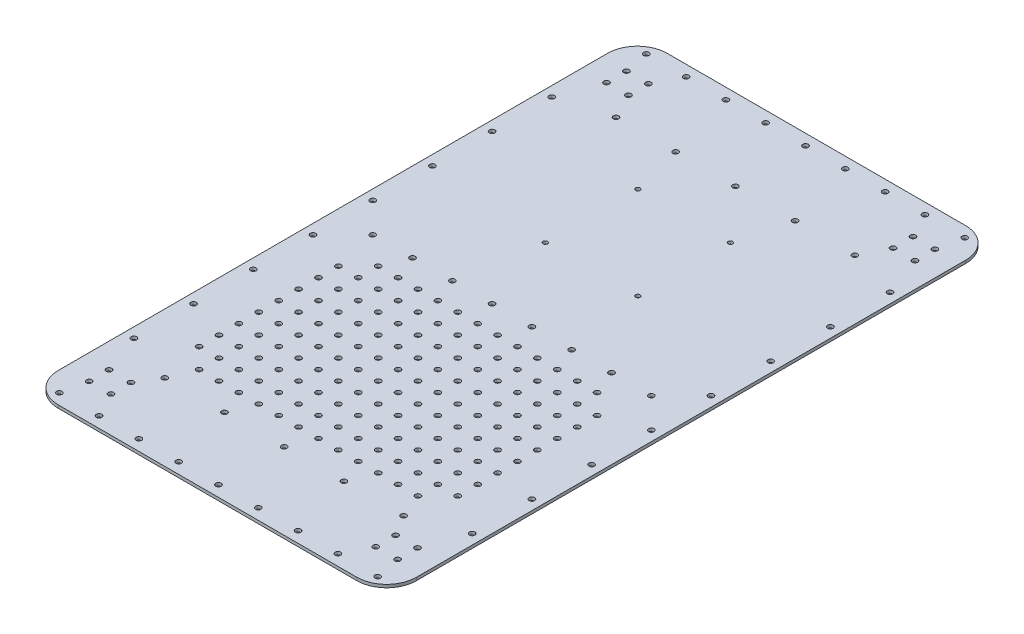
SolidWorks part; units mm, degrees
ref_plane "前视基准面" through (0, 0, 0) normal (0, 0, 1) x (1, 0, 0)
ref_plane "上视基准面" through (0, 0, 0) normal (0, 1, 0) x (1, 0, 0)
ref_plane "右视基准面" through (0, 0, 0) normal (1, 0, 0) x (0, 0, -1)
sketch "Sketch1" plane through (0, 0, 0) normal (0, 1, 0) x (1, 0, 0)
  line L0 (0, 430.9523) -> (0, 0) construction
  line L1 (-180, 306) -> (180, 306)
  line L2 (-180, 306) -> (-180, -306)
  line L3 (-180, -306) -> (180, -306)
  line L4 (180, 306) -> (180, -306)
  line L5 (-180, 306) -> (180, -306) construction
  line L6 (-180, -306) -> (180, 306) construction
  line L7 (133, -250) -> (155, -250) construction
  line L8 (133, -250) -> (133, -270) construction
  line L9 (133, -270) -> (155, -270) construction
  line L10 (155, -250) -> (155, -270) construction
  line L11 (133, -250) -> (155, -270) construction
  line L12 (133, -270) -> (155, -250) construction
  line L13 (0, 0) -> (392.7159, 0) construction
  circle A0 centre (133, -250) radius 2.75
  circle A1 centre (155, -250) radius 2.75
  circle A2 centre (133, -270) radius 2.75
  circle A3 centre (155, -270) radius 2.75
  circle A4 centre (155, 270) radius 2.75
  circle A5 centre (133, 270) radius 2.75
  circle A6 centre (155, 250) radius 2.75
  circle A7 centre (133, 250) radius 2.75
  circle A8 centre (-155, 250) radius 2.75
  circle A9 centre (-133, 250) radius 2.75
  circle A10 centre (-155, 270) radius 2.75
  circle A11 centre (-133, 270) radius 2.75
  circle A12 centre (-155, -270) radius 2.75
  circle A13 centre (-133, -270) radius 2.75
  circle A14 centre (-155, -250) radius 2.75
  circle A15 centre (-133, -250) radius 2.75
  point P0 (0, 0)
  point P6 (144, -260)
  dimension "D5" = 5.5
  dimension "D1" = 612
  dimension "D2" = 360
  dimension "D3" = 22
  dimension "D4" = 20
  dimension "D6" = 46
  dimension "D7" = 36
extrude "Boss-Extrude1" add sketch "Sketch1" along normal blind 3
sketch "草图1" plane through (0, 3, 0) normal (0, 1, 0) x (1, 0, 0)
  line L0 (-170, 306) -> (-170, -306) construction
  line L1 (180, 306) -> (-180, 306) construction
  line L2 (-180, -306) -> (180, -306) construction
  line L3 (-180, 306) -> (-180, -306) construction
  line L4 (0, 306) -> (0, -306) construction
  line L5 (-280.0781, 0) -> (279.3653, 0) construction
  circle A0 centre (-170, 210) radius 2.75
  circle A1 centre (-170, 150) radius 2.75
  circle A2 centre (-170, 90) radius 2.75
  circle A3 centre (-170, 30) radius 2.75
  circle A4 centre (-170, -30) radius 2.75
  circle A5 centre (-170, -90) radius 2.75
  circle A6 centre (-170, -150) radius 2.75
  circle A7 centre (-170, -210) radius 2.75
  circle A8 centre (170, -210) radius 2.75
  circle A9 centre (170, -150) radius 2.75
  circle A10 centre (170, -90) radius 2.75
  circle A11 centre (170, -30) radius 2.75
  circle A12 centre (170, 30) radius 2.75
  circle A13 centre (170, 90) radius 2.75
  circle A14 centre (170, 150) radius 2.75
  circle A15 centre (170, 210) radius 2.75
  dimension "D2" = 5.5
  dimension "D1" = 10
  dimension "D3" = 60
  dimension "D4" = 8
extrude "切除-拉伸1" cut sketch "草图1" against normal through all
sketch "Sketch2" plane through (0, 3, 0) normal (0, 1, 0) x (1, 0, 0)
  line L0 (-180, -295) -> (180, -295) construction
  line L1 (-180, 306) -> (-180, -306) construction
  line L2 (180, -306) -> (180, 306) construction
  line L3 (-180, -306) -> (180, -306) construction
  line L4 (-329.001, 0) -> (494.6921, 0) construction
  line L5 (-180, 295) -> (180, 295) construction
  line L6 (0, 129.5767) -> (0, -107.5451) construction
  circle A0 centre (-160, -295) radius 2.75
  circle A1 centre (-120, -295) radius 2.75
  circle A2 centre (-80, -295) radius 2.75
  circle A3 centre (-40, -295) radius 2.75
  circle A4 centre (0, -295) radius 2.75
  circle A5 centre (40, -295) radius 2.75
  circle A6 centre (80, -295) radius 2.75
  circle A7 centre (120, -295) radius 2.75
  circle A8 centre (160, -295) radius 2.75
  circle A20 centre (510, 295) radius 2.75
  circle A21 centre (470, 295) radius 2.75
  circle A22 centre (430, 295) radius 2.75
  circle A23 centre (390, 295) radius 2.75
  circle A24 centre (350, 295) radius 2.75
  circle A25 centre (310, 295) radius 2.75
  circle A26 centre (270, 295) radius 2.75
  circle A27 centre (230, 295) radius 2.75
  circle A28 centre (190, 295) radius 2.75
  circle A29 centre (160, 295) radius 2.75
  circle A30 centre (120, 295) radius 2.75
  circle A31 centre (80, 295) radius 2.75
  circle A32 centre (40, 295) radius 2.75
  circle A33 centre (0, 295) radius 2.75
  circle A34 centre (-40, 295) radius 2.75
  circle A35 centre (-80, 295) radius 2.75
  circle A36 centre (-120, 295) radius 2.75
  circle A37 centre (-160, 295) radius 2.75
  circle A40 centre (-20, 0) radius 2.75
  circle A41 centre (-60, 0) radius 2.75
  circle A42 centre (-100, 0) radius 2.75
  circle A43 centre (-140, 0) radius 2.75
  circle A44 centre (140, 0) radius 2.75
  circle A45 centre (100, 0) radius 2.75
  circle A46 centre (60, 0) radius 2.75
  circle A47 centre (20, 0) radius 2.75
  dimension "D2" = 5.5
  dimension "D6" = 5.5
  dimension "D1" = 11
  dimension "D3" = 20
  dimension "D5" = 40
  dimension "D7" = 20
  dimension "D9" = 40
  dimension "D4" = 9
  dimension "D8" = 4
extrude "Cut-Extrude1" cut sketch "Sketch2" against normal through all
fillet "Fillet1" radius 30 4 edges at (-180, 1.5, 306) (180, 1.5, 306) (180, 1.5, -306) (-180, 1.5, -306)
sketch "Sketch3" plane through (0, 3, 0) normal (0, 1, 0) x (1, 0, 0)
  line L0 (0, 424.2125) -> (0, -501.4745) construction
  line L1 (-336.746, 0) -> (500.0168, 0) construction
  line L2 (0, 173) -> (0, -28.2463) construction
  line L3 (-46.5, 173) -> (46.5, 173) construction
  line L4 (-46.5, 173) -> (-46.5, 80) construction
  line L5 (-46.5, 80) -> (46.5, 80) construction
  line L6 (46.5, 173) -> (46.5, 80) construction
  circle A0 centre (-46.5, 173) radius 2.25
  circle A1 centre (46.5, 173) radius 2.25
  circle A2 centre (-46.5, 80) radius 2.25
  circle A3 centre (46.5, 80) radius 2.25
  dimension "D5" = 4.5
  dimension "D1" = 93
  dimension "D2" = 93
  dimension "D3" = 80
extrude "Cut-Extrude2" cut sketch "Sketch3" against normal through all both and the other way through all
sketch "Sketch5" plane through (0, 3, 0) normal (0, 1, 0) x (1, 0, 0)
  line L0 (0, 0) -> (0, -337.371) construction
  line L1 (-232.7509, -4.5) -> (285.177, -4.5) construction
  line L2 (133, -250) -> (133, -270) construction
  line L3 (-110, -224.5) -> (110, -224.5) construction
  line L4 (-150, -306) -> (150, -306) construction
  line L5 (-180, 0) -> (342.3695, 0) construction
  line L6 (-180, 276) -> (-180, -276) construction
  line L7 (-194.3384, -229) -> (315.9326, -229) construction
  circle A0 centre (-10, -4.5) radius 2.75 construction
  circle A1 centre (-30, -4.5) radius 2.75 construction
  circle A2 centre (-50, -4.5) radius 2.75 construction
  circle A3 centre (-70, -4.5) radius 2.75 construction
  circle A4 centre (-90, -4.5) radius 2.75 construction
  circle A5 centre (-110, -4.5) radius 2.75 construction
  circle A6 centre (-130, -4.5) radius 2.75 construction
  circle A7 centre (-30, -24.5) radius 2.75
  circle A8 centre (-50, -24.5) radius 2.75
  circle A9 centre (-70, -24.5) radius 2.75
  circle A10 centre (-90, -24.5) radius 2.75
  circle A11 centre (-110, -24.5) radius 2.75
  circle A12 centre (-130, -24.5) radius 2.75 construction
  circle A13 centre (-30, -44.5) radius 2.75
  circle A14 centre (-50, -44.5) radius 2.75
  circle A15 centre (-70, -44.5) radius 2.75
  circle A16 centre (-90, -44.5) radius 2.75
  circle A17 centre (-110, -44.5) radius 2.75
  circle A18 centre (-130, -44.5) radius 2.75
  circle A19 centre (-30, -64.5) radius 2.75
  circle A20 centre (-50, -64.5) radius 2.75
  circle A21 centre (-70, -64.5) radius 2.75
  circle A22 centre (-90, -64.5) radius 2.75
  circle A23 centre (-110, -64.5) radius 2.75
  circle A24 centre (-130, -64.5) radius 2.75
  circle A25 centre (-30, -84.5) radius 2.75
  circle A26 centre (-50, -84.5) radius 2.75
  circle A27 centre (-70, -84.5) radius 2.75
  circle A28 centre (-90, -84.5) radius 2.75
  circle A29 centre (-110, -84.5) radius 2.75
  circle A30 centre (-130, -84.5) radius 2.75
  circle A31 centre (-30, -104.5) radius 2.75
  circle A32 centre (-50, -104.5) radius 2.75
  circle A33 centre (-70, -104.5) radius 2.75
  circle A34 centre (-90, -104.5) radius 2.75
  circle A35 centre (-110, -104.5) radius 2.75
  circle A36 centre (-130, -104.5) radius 2.75
  circle A37 centre (-30, -124.5) radius 2.75
  circle A38 centre (-50, -124.5) radius 2.75
  circle A39 centre (-70, -124.5) radius 2.75
  circle A40 centre (-90, -124.5) radius 2.75
  circle A41 centre (-110, -124.5) radius 2.75
  circle A42 centre (-130, -124.5) radius 2.75
  circle A43 centre (-30, -144.5) radius 2.75
  circle A44 centre (-50, -144.5) radius 2.75
  circle A45 centre (-70, -144.5) radius 2.75
  circle A46 centre (-90, -144.5) radius 2.75
  circle A47 centre (-110, -144.5) radius 2.75
  circle A48 centre (-130, -144.5) radius 2.75
  circle A49 centre (-30, -164.5) radius 2.75
  circle A50 centre (-50, -164.5) radius 2.75
  circle A51 centre (-70, -164.5) radius 2.75
  circle A52 centre (-90, -164.5) radius 2.75
  circle A53 centre (-110, -164.5) radius 2.75
  circle A54 centre (-130, -164.5) radius 2.75
  circle A55 centre (-30, -184.5) radius 2.75
  circle A56 centre (-50, -184.5) radius 2.75
  circle A57 centre (-70, -184.5) radius 2.75
  circle A58 centre (-90, -184.5) radius 2.75
  circle A59 centre (-110, -184.5) radius 2.75
  circle A60 centre (-130, -184.5) radius 2.75
  circle A61 centre (-10, -24.5) radius 2.75
  circle A62 centre (-10, -44.5) radius 2.75
  circle A63 centre (-10, -64.5) radius 2.75
  circle A64 centre (-10, -84.5) radius 2.75
  circle A65 centre (-10, -104.5) radius 2.75
  circle A66 centre (-10, -124.5) radius 2.75
  circle A67 centre (-10, -144.5) radius 2.75
  circle A68 centre (-10, -164.5) radius 2.75
  circle A69 centre (-10, -184.5) radius 2.75
  circle A70 centre (10, -184.5) radius 2.75
  circle A71 centre (10, -164.5) radius 2.75
  circle A72 centre (10, -144.5) radius 2.75
  circle A73 centre (10, -124.5) radius 2.75
  circle A74 centre (10, -104.5) radius 2.75
  circle A75 centre (10, -84.5) radius 2.75
  circle A76 centre (10, -64.5) radius 2.75
  circle A77 centre (10, -44.5) radius 2.75
  circle A78 centre (10, -24.5) radius 2.75
  circle A79 centre (130, -184.5) radius 2.75
  circle A80 centre (110, -184.5) radius 2.75
  circle A81 centre (90, -184.5) radius 2.75
  circle A82 centre (70, -184.5) radius 2.75
  circle A83 centre (50, -184.5) radius 2.75
  circle A84 centre (30, -184.5) radius 2.75
  circle A85 centre (130, -164.5) radius 2.75
  circle A86 centre (110, -164.5) radius 2.75
  circle A87 centre (90, -164.5) radius 2.75
  circle A88 centre (70, -164.5) radius 2.75
  circle A89 centre (50, -164.5) radius 2.75
  circle A90 centre (30, -164.5) radius 2.75
  circle A91 centre (130, -144.5) radius 2.75
  circle A92 centre (110, -144.5) radius 2.75
  circle A93 centre (90, -144.5) radius 2.75
  circle A94 centre (70, -144.5) radius 2.75
  circle A95 centre (50, -144.5) radius 2.75
  circle A96 centre (30, -144.5) radius 2.75
  circle A97 centre (130, -124.5) radius 2.75
  circle A98 centre (110, -124.5) radius 2.75
  circle A99 centre (90, -124.5) radius 2.75
  circle A100 centre (70, -124.5) radius 2.75
  circle A101 centre (50, -124.5) radius 2.75
  circle A102 centre (30, -124.5) radius 2.75
  circle A103 centre (130, -104.5) radius 2.75
  circle A104 centre (110, -104.5) radius 2.75
  circle A105 centre (90, -104.5) radius 2.75
  circle A106 centre (70, -104.5) radius 2.75
  circle A107 centre (50, -104.5) radius 2.75
  circle A108 centre (30, -104.5) radius 2.75
  circle A109 centre (130, -84.5) radius 2.75
  circle A110 centre (110, -84.5) radius 2.75
  circle A111 centre (90, -84.5) radius 2.75
  circle A112 centre (70, -84.5) radius 2.75
  circle A113 centre (50, -84.5) radius 2.75
  circle A114 centre (30, -84.5) radius 2.75
  circle A115 centre (130, -64.5) radius 2.75
  circle A116 centre (110, -64.5) radius 2.75
  circle A117 centre (90, -64.5) radius 2.75
  circle A118 centre (70, -64.5) radius 2.75
  circle A119 centre (50, -64.5) radius 2.75
  circle A120 centre (30, -64.5) radius 2.75
  circle A121 centre (130, -44.5) radius 2.75
  circle A122 centre (110, -44.5) radius 2.75
  circle A123 centre (90, -44.5) radius 2.75
  circle A124 centre (70, -44.5) radius 2.75
  circle A125 centre (50, -44.5) radius 2.75
  circle A126 centre (30, -44.5) radius 2.75
  circle A127 centre (130, -24.5) radius 2.75 construction
  circle A128 centre (110, -24.5) radius 2.75
  circle A129 centre (90, -24.5) radius 2.75
  circle A130 centre (70, -24.5) radius 2.75
  circle A131 centre (50, -24.5) radius 2.75
  circle A132 centre (30, -24.5) radius 2.75
  circle A133 centre (130, -4.5) radius 2.75 construction
  circle A134 centre (110, -4.5) radius 2.75 construction
  circle A135 centre (90, -4.5) radius 2.75 construction
  circle A136 centre (70, -4.5) radius 2.75 construction
  circle A137 centre (50, -4.5) radius 2.75 construction
  circle A138 centre (30, -4.5) radius 2.75 construction
  circle A139 centre (10, -4.5) radius 2.75 construction
  circle A140 centre (-10, -204.5) radius 2.75
  circle A141 centre (-30, -204.5) radius 2.75
  circle A142 centre (-50, -204.5) radius 2.75
  circle A143 centre (-70, -204.5) radius 2.75
  circle A144 centre (-90, -204.5) radius 2.75
  circle A145 centre (-110, -204.5) radius 2.75
  circle A147 centre (-10, -224.5) radius 2.75 construction
  circle A148 centre (-30, -224.5) radius 2.75 construction
  circle A149 centre (-50, -224.5) radius 2.75 construction
  circle A150 centre (-70, -224.5) radius 2.75 construction
  circle A151 centre (-90, -224.5) radius 2.75 construction
  circle A152 centre (-110, -224.5) radius 2.75 construction
  circle A155 centre (110, -224.5) radius 2.75 construction
  circle A156 centre (90, -224.5) radius 2.75 construction
  circle A157 centre (70, -224.5) radius 2.75 construction
  circle A158 centre (50, -224.5) radius 2.75 construction
  circle A159 centre (30, -224.5) radius 2.75 construction
  circle A160 centre (10, -224.5) radius 2.75 construction
  circle A162 centre (110, -204.5) radius 2.75
  circle A163 centre (90, -204.5) radius 2.75
  circle A164 centre (70, -204.5) radius 2.75
  circle A165 centre (50, -204.5) radius 2.75
  circle A166 centre (30, -204.5) radius 2.75
  circle A167 centre (10, -204.5) radius 2.75
  circle A168 centre (-130, -204.5) radius 2.75 [skipped]
  circle A169 centre (-130, -224.5) radius 2.75 [skipped]
  circle A170 centre (-120, -224.5) radius 2.75 construction
  circle A171 centre (-60, -224.5) radius 2.75 construction
  circle A172 centre (0, -224.5) radius 2.75 construction
  circle A173 centre (60, -224.5) radius 2.75 construction
  circle A174 centre (120, -224.5) radius 2.75 construction
  circle A180 centre (120, 224.5) radius 2.75
  circle A181 centre (0, 224.5) radius 2.75
  circle A182 centre (-60, 224.5) radius 2.75
  circle A183 centre (-120, 224.5) radius 2.75
  circle A184 centre (60, 224.5) radius 2.75
  circle A185 centre (0, -229) radius 2.75
  circle A186 centre (-60, -229) radius 2.75
  circle A187 centre (-120, -229) radius 2.75
  circle A188 centre (120, -229) radius 2.75
  circle A189 centre (60, -229) radius 2.75
  dimension "D2" = 5.5
  dimension "D8" = 5
  dimension "D10" = 77
  dimension "D11" = 60
  dimension "D1" = 81.5
  dimension "D3" = 10
  dimension "D6" = 20
  dimension "D7" = 20
  dimension "D9" = 60
  dimension "D12" = 60
  dimension "D4" = 7
  dimension "D5" = 12
extrude "Cut-Extrude3" cut sketch "Sketch5" against normal through all
